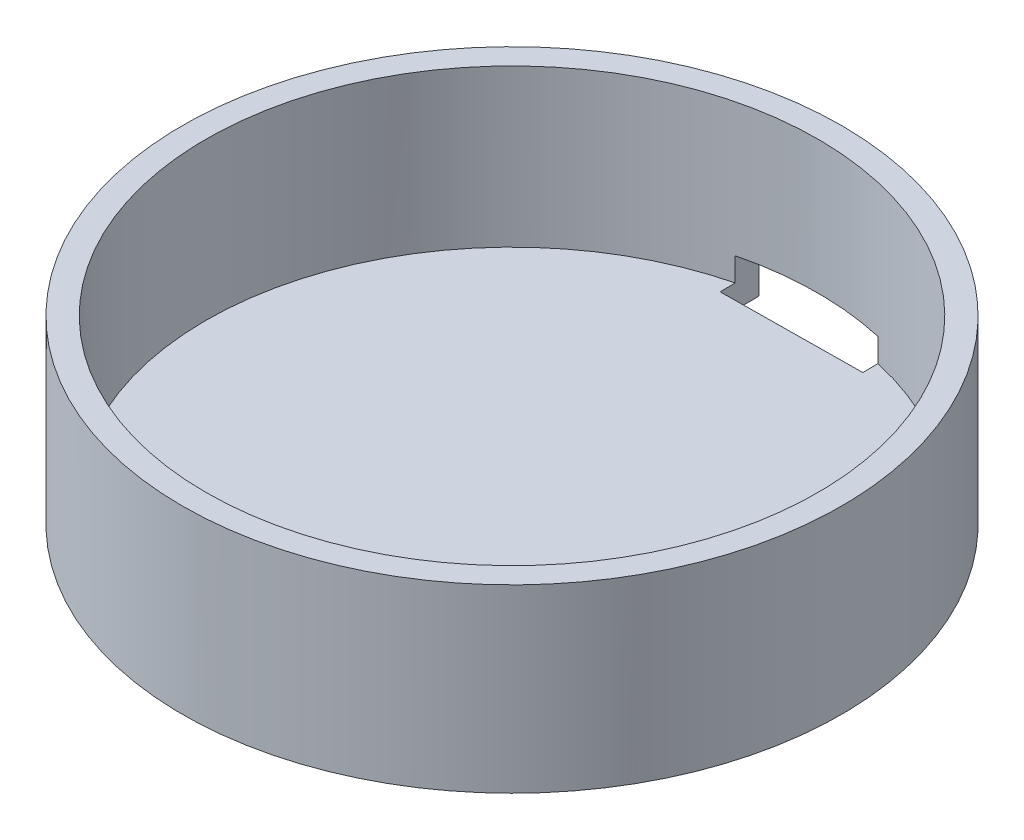
SolidWorks part; units mm, degrees
ref_plane "Front Plane" through (0, 0, 0) normal (0, 0, 1) x (1, 0, 0)
ref_plane "Top Plane" through (0, 0, 0) normal (0, 1, 0) x (1, 0, 0)
ref_plane "Right Plane" through (0, 0, 0) normal (1, 0, 0) x (0, 0, -1)
sketch "Sketch1" plane through (0, 0, 0) normal (0, 1, 0) x (1, 0, 0)
  circle A0 centre (0, 0) radius 19.5
  dimension "D1" = 39
extrude "Boss-Extrude1" add sketch "Sketch1" along normal blind 10
shell "Shell1" thickness 1.5
sketch "Sketch2" plane through (-35.1178, 32.6042, -20.6275) normal (-0.0106, 0, -0.9999) x (-0.9999, 0, 0.0106)
  line L0 (-55.8964, -34.1042) -> (-13.8964, -34.1042) construction
  line L1 (-39.3964, -31.1042) -> (-30.3964, -31.1042)
  line L2 (-39.3964, -31.1042) -> (-39.3964, -37.1042)
  line L3 (-39.3964, -37.1042) -> (-30.3964, -37.1042)
  line L4 (-30.3964, -31.1042) -> (-30.3964, -37.1042)
  line L5 (-34.8964, -37.1042) -> (-34.8964, -31.1042) construction
  line L6 (-39.3964, -34.1042) -> (-30.3964, -34.1042) construction
  point P0 (-34.8964, -34.1042)
  dimension "D1" = 9
  dimension "D2" = 6
extrude "Cut-Extrude1" cut sketch "Sketch2" against normal blind 3
